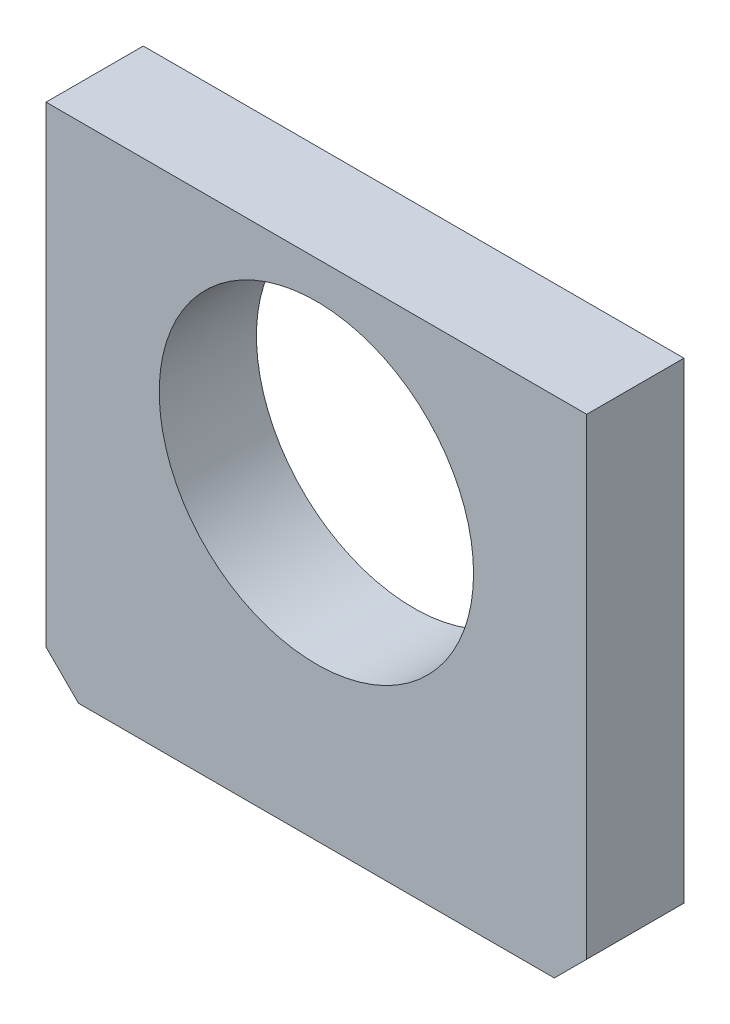
SolidWorks part; units mm, degrees
material "Beech"
ref_plane "Front Plane" through (0, 0, 0) normal (0, 0, 1) x (1, 0, 0)
ref_plane "Top Plane" through (0, 0, 0) normal (0, 1, 0) x (1, 0, 0)
ref_plane "Right Plane" through (0, 0, 0) normal (1, 0, 0) x (0, 0, -1)
sketch "Sketch1" plane through (0, 0, 0) normal (0, 0, 1) x (1, 0, 0)
  line L1 (52.975, 495.5063) -> (-52.975, 495.5063)
  line L2 (52.975, 495.5063) -> (52.975, 396.6626)
  line L3 (52.975, 396.6626) -> (-52.975, 396.6626)
  line L4 (-52.975, 495.5063) -> (-52.975, 396.6626)
extrude "Boss-Extrude1" add sketch "Sketch1" against normal blind 19.05
sketch "Sketch2" plane through (0, 0, 0) normal (0, 0, 1) x (1, 0, 0)
  circle A0 centre (0, 457.4063) radius 30.7975
  circle A1 centre (0, 457.4063) radius 30.7975 construction
extrude "Cut-Extrude1" cut sketch "Sketch2" against normal through all
chamfer "Chamfer1" distance 6.35 angle 45 2 edges at (52.975, 396.6626, -9.525) (-52.975, 396.6626, -9.525)
